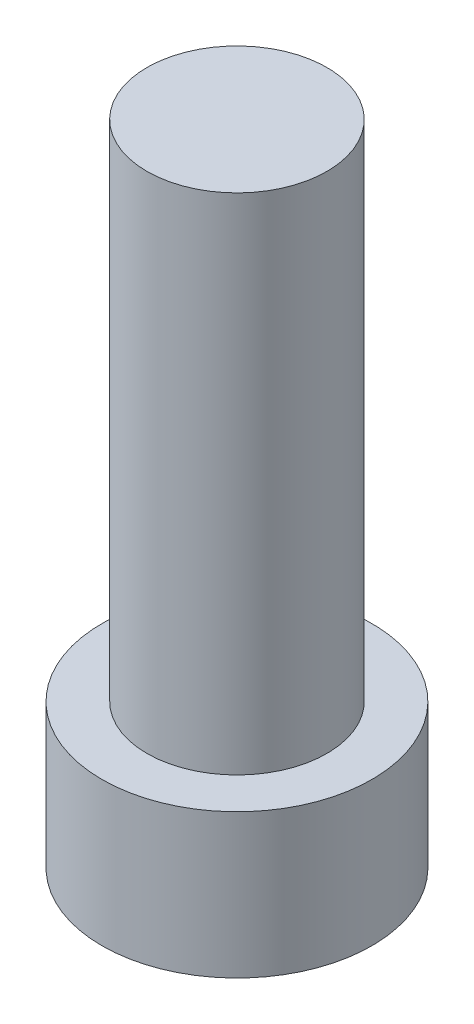
SolidWorks part; units mm, degrees
material "AISI 1020"
ref_plane "前视基准面" through (0, 0, 0) normal (0, 0, 1) x (1, 0, 0)
ref_plane "上视基准面" through (0, 0, 0) normal (0, 1, 0) x (1, 0, 0)
ref_plane "右视基准面" through (0, 0, 0) normal (1, 0, 0) x (0, 0, -1)
other "Configuration Table"
sketch "草图1" plane through (0, 0, 0) normal (0, 1, 0) x (1, 0, 0)
  circle A0 centre (0, 0) radius 3.75
  dimension "D1" = 7.5
extrude "凸台-拉伸1" add sketch "草图1" along normal blind 4
sketch "草图2" plane through (0, 4, 0) normal (0, 1, 0) x (1, 0, 0)
  circle A0 centre (0, 0) radius 2.5
  dimension "D1" = 5
extrude "凸台-拉伸2" add sketch "草图2" along normal blind 14
sketch "草图3" plane through (0, 0, 0) normal (0, -1, 0) x (1, 0, 0)
  line L1 (1.2415, 2.17) -> (-1.2585, 2.1602)
  line L2 (-1.2585, 2.1602) -> (-2.5, -0.0098)
  line L3 (-2.5, -0.0098) -> (-1.2415, -2.17)
  line L4 (-1.2415, -2.17) -> (1.2585, -2.1602)
  line L5 (1.2585, -2.1602) -> (2.5, 0.0098)
  line L6 (2.5, 0.0098) -> (1.2415, 2.17)
  circle A0 centre (0, 0) radius 2.1651 construction
  point P1 (1.2295, 2.066)
  dimension "D1" = 2.5
extrude "切除-拉伸1" cut sketch "草图3" against normal blind 2.5
fillet "圆角1" radius 0.1 6 edges at (-1.8708, 0, -1.0899) (0.0085, 0, -2.1651) (1.8792, 0, -1.0752) (1.8708, 0, 1.0899) (-1.8792, 0, 1.0752) (-0.0085, 0, 2.1651)
